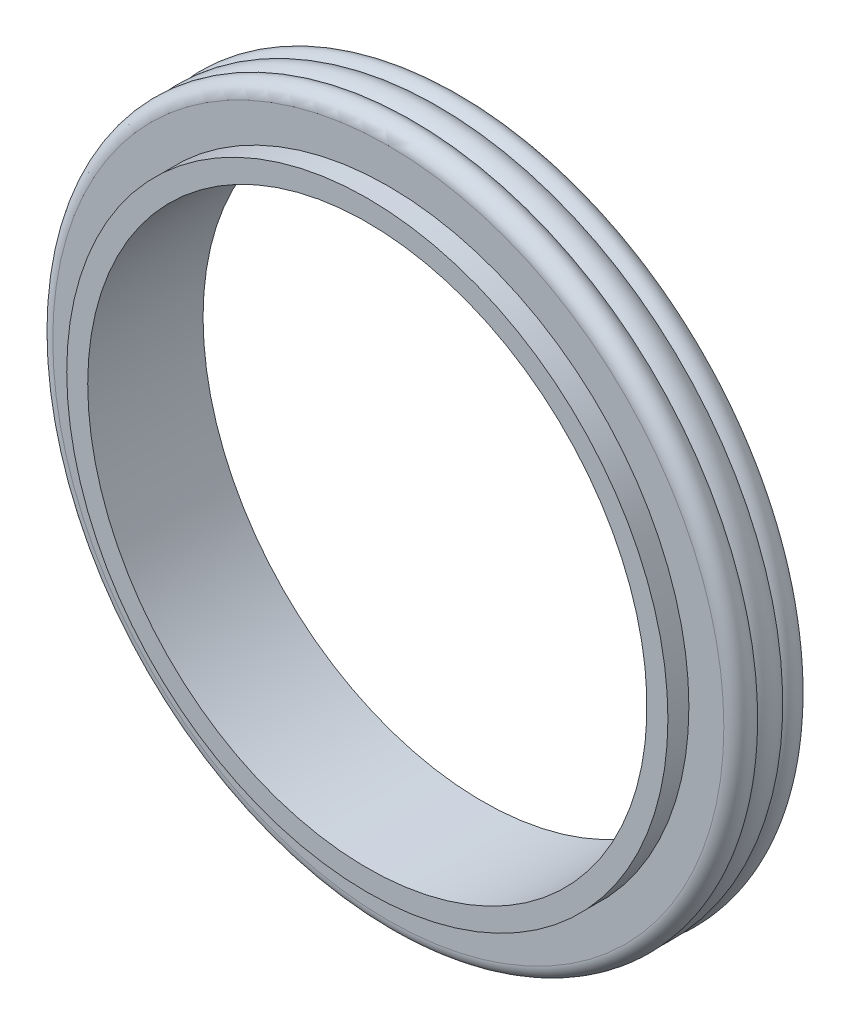
SolidWorks part; units mm, degrees
ref_plane "Front Plane" through (0, 0, 0) normal (0, 0, 1) x (1, 0, 0)
ref_plane "Top Plane" through (0, 0, 0) normal (0, 1, 0) x (1, 0, 0)
ref_plane "Right Plane" through (0, 0, 0) normal (1, 0, 0) x (0, 0, -1)
sketch "Sketch1" plane through (0, 0, 0) normal (1, 0, 0) x (0, 0, -1)
  line L0 (0, 40) -> (0, -42.8872) construction
  line L1 (8.25, 40) -> (-8.25, 40)
  line L2 (-8.25, 40) -> (-8.25, 43)
  line L3 (-8.25, 43) -> (-5.25, 43)
  line L4 (-5.25, 43) -> (-5.25, 48)
  line L5 (8.25, 40) -> (8.25, 43)
  line L6 (8.25, 43) -> (5.25, 43)
  line L7 (5.25, 43) -> (5.25, 48)
  line L8 (0, 0) -> (-31.8056, 0) construction
  arc A3 (-5.25, 48) -> (-1.8, 49.3775) centre (-3.25, 48) cw
  arc A4 (5.25, 48) -> (1.8, 49.3775) centre (3.25, 48) ccw
  arc A5 (-1.8, 49.3775) -> (1.8, 49.3775) centre (0, 46.9775) cw
  dimension "D3" = 3
  dimension "D6" = 2
  dimension "D8" = 3
  dimension "D1" = 40
  dimension "D2" = 8.25
  dimension "D4" = 5
  dimension "D5" = 3.45
  dimension "D7" = 3
revolve "Revolve1" add sketch "Sketch1" angle 360 about L8
